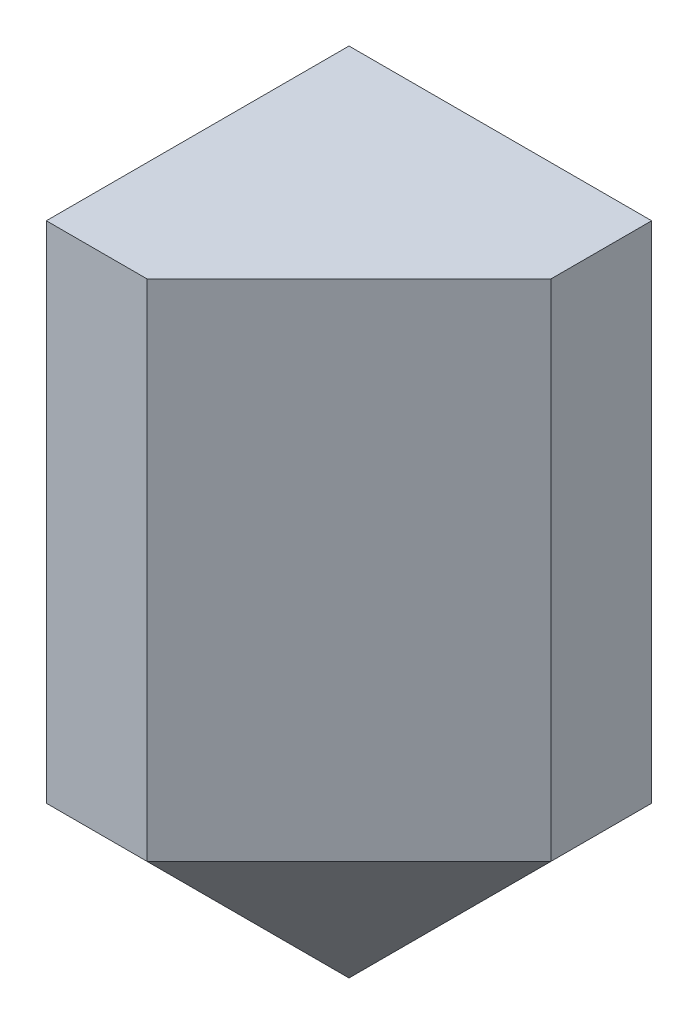
SolidWorks part; units mm, degrees
material "ABS generico"
ref_plane "Piano frontale" through (0, 0, 0) normal (0, 0, 1) x (1, 0, 0)
ref_plane "Piano superiore" through (0, 0, 0) normal (0, 1, 0) x (1, 0, 0)
ref_plane "Piano destro" through (0, 0, 0) normal (1, 0, 0) x (0, 0, -1)
sketch "Schizzo1" plane through (0, 0, 0) normal (0, 0, 1) x (1, 0, 0)
  line L1 (0, 0) -> (30, 0)
  line L2 (0, 0) -> (0, 40)
  line L3 (0, 40) -> (30, 40)
  line L4 (30, 0) -> (30, 40)
  dimension "D1" = 30
  dimension "D2" = 40
extrude "Estrusione-Estrusione1" add sketch "Schizzo1" along normal blind 30
chamfer "Smusso1" distance 20 angle 45 3 edges at (30, 20, 30) (30, 0, 15) (15, 0, 30)
sketch "Schizzo2" plane through (0, 40, 0) normal (0, 1, 0) x (1, 0, 0)
  line L0 (0, 0) -> (30, 0)
  line L1 (30, 0) -> (30, -10)
  line L2 (30, -10) -> (10, -30)
  line L3 (10, -30) -> (0, -30)
  line L4 (0, -30) -> (0, 0)
extrude "Estrusione-Estrusione2" add sketch "Schizzo2" along normal blind 30
hole_wizard "Foro per Vite M5-1" positions "Schizzo3" profile "Schizzo4" hole size "M5" standard "ISO"
sketch "Schizzo3" plane through (0, 0, 0) normal (-1, 0, 0) x (0, 0, 1)
  line L0 (18, 20) -> (18, 34) construction
  line L2 (0, 70) -> (0, 0) construction
  line L4 (18, 48) -> (18, 34) construction
  line L5 (0, 70) -> (30, 70) construction
  point P0 (18, 20)
  point P28 (18, 48)
  point P33 (0, 0)
  dimension "D1" = 18
  dimension "D2" = 22
  dimension "D3" = 14
  dimension "D4" = 14
sketch "Schizzo4" plane through (0, 20, 18) normal (0, 1, 0) x (0, 0, 1)
  line L0 (0, 0) -> (0, 16.6524)
  line L1 (0, 16.6524) -> (2.75, 15)
  line L2 (2.75, 15) -> (2.75, 0)
  line L5 (2.75, 0) -> (0, 0)
  line L10 (0, 16.6524) -> (-2.75, 15) construction
  line L11 (0, -6.35) -> (0, 107.95) construction
  dimension "Hole Dia." = 5.5
  dimension "Hole Depth" = 15
  dimension "Drill Angle" = 118
hole_wizard "Foro per Vite M5-2" positions "Schizzo3D1" profile "Schizzo5" hole size "M5" standard "ISO"
sketch3d "Schizzo3D1"
  line L4 (30, 70, 0) -> (0, 70, 0) construction
  line L5 (0, 70, 0) -> (0, 0, 0) construction
  point P2 (18, 20, 0)
  point P13 (0, 0, 0)
  dimension "D1" = 50
  dimension "D2" = 18
sketch "Schizzo5" plane through (18, 20, 0) normal (1, 0, 0) x (0, 1, 0)
  line L0 (0, 0) -> (0, 16.6524)
  line L1 (0, 16.6524) -> (2.75, 15)
  line L2 (2.75, 15) -> (2.75, 0)
  line L5 (2.75, 0) -> (0, 0)
  line L10 (0, 16.6524) -> (-2.75, 15) construction
  line L11 (0, -6.35) -> (0, 107.95) construction
  dimension "Hole Dia." = 5.5
  dimension "Hole Depth" = 15
  dimension "Drill Angle" = 118
sketch "Schizzo6" plane through (0, 0, 0) normal (0, 0, -1) x (-1, 0, 0)
  line L0 (-30, 20) -> (-30, 70) construction
  line L1 (-30, 70) -> (0, 70) construction
  circle A0 centre (-15, 55) radius 10
  dimension "D1" = 15
  dimension "D3" = 20
  dimension "D2" = 15
extrude "Taglio-Estrusione1" cut sketch "Schizzo6" against normal blind 2
